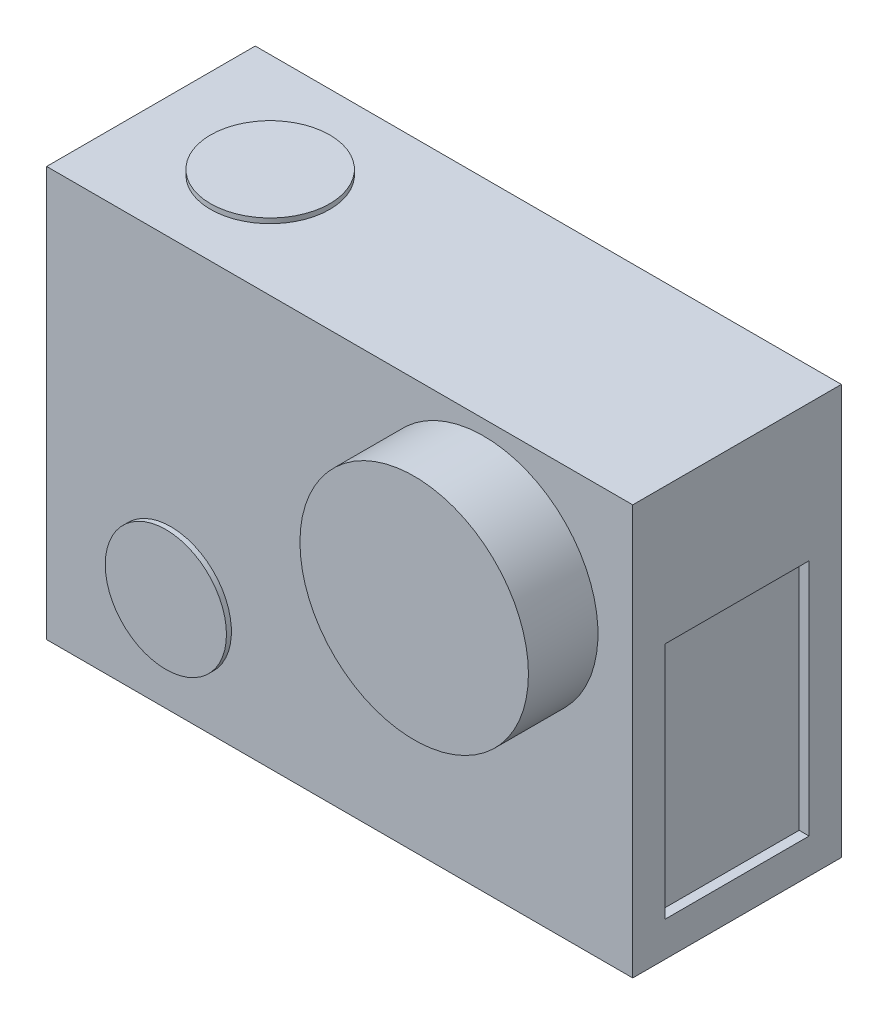
SolidWorks part; units mm, degrees
ref_plane "Front Plane" through (0, 0, 0) normal (0, 0, 1) x (1, 0, 0)
ref_plane "Top Plane" through (0, 0, 0) normal (0, 1, 0) x (1, 0, 0)
ref_plane "Right Plane" through (0, 0, 0) normal (1, 0, 0) x (0, 0, -1)
sketch "Sketch1" plane through (0, 0, 0) normal (0, 0, 1) x (1, 0, 0)
  line L1 (29.5, 20.625) -> (-29.5, 20.625)
  line L2 (29.5, 20.625) -> (29.5, -20.625)
  line L3 (29.5, -20.625) -> (-29.5, -20.625)
  line L4 (-29.5, 20.625) -> (-29.5, -20.625)
  line L5 (29.5, 20.625) -> (-29.5, -20.625) construction
  line L6 (29.5, -20.625) -> (-29.5, 20.625) construction
  point P0 (0, 0)
  dimension "D1" = 59
  dimension "D2" = 41.25
extrude "Boss-Extrude1" add sketch "Sketch1" along normal blind 21
sketch "Sketch2" plane through (0, 0, 21) normal (0, 0, 1) x (1, 0, 0)
  line L0 (29.5, -20.625) -> (29.5, 20.625) construction
  line L1 (29.5, 20.625) -> (-29.5, 20.625) construction
  circle A0 centre (14.5, 7.625) radius 11.5
  dimension "D3" = 23
  dimension "D1" = 15
  dimension "D2" = 13
extrude "Boss-Extrude2" add sketch "Sketch2" along normal blind 7
sketch "Sketch3" plane through (0, 0, 21) normal (0, 0, 1) x (1, 0, 0)
  line L0 (-29.5, 20.625) -> (-29.5, -20.625) construction
  line L2 (-29.5, -20.625) -> (29.5, -20.625) construction
  circle A0 centre (-17, -10.625) radius 6.1
  dimension "D3" = 12.2
  dimension "D1" = 12.5
  dimension "D2" = 10
extrude "Boss-Extrude3" add sketch "Sketch3" along normal blind 0.5
sketch "Sketch4" plane through (29.5, 0, 0) normal (1, 0, 0) x (0, 0, -1)
  line L0 (-10.5, 20.625) -> (-10.5, -49979.375) construction
  line L1 (-17.75, 6.875) -> (-3.25, 6.875)
  line L2 (-17.75, 6.875) -> (-17.75, -17.125)
  line L3 (-17.75, -17.125) -> (-3.25, -17.125)
  line L4 (-3.25, 6.875) -> (-3.25, -17.125)
  line L5 (-21, 20.625) -> (0, 20.625) construction
  line L6 (-21, -20.625) -> (0, -20.625) construction
  point P8 (-10.5, 20.625)
  dimension "D1" = 24
  dimension "D2" = 14.5
  dimension "D3" = 3.5
extrude "Cut-Extrude1" cut sketch "Sketch4" against normal blind 1
sketch "Sketch5" plane through (0, 0, 0) normal (0, 0, -1) x (-1, 0, 0)
  line L1 (23.5, 18.25) -> (-23.5, 18.25)
  line L2 (23.5, 18.25) -> (23.5, -18.25)
  line L3 (23.5, -18.25) -> (-23.5, -18.25)
  line L4 (-23.5, 18.25) -> (-23.5, -18.25)
  line L5 (23.5, 18.25) -> (-23.5, -18.25) construction
  line L6 (23.5, -18.25) -> (-23.5, 18.25) construction
  point P0 (0, 0)
  dimension "D1" = 47
  dimension "D2" = 36.5
extrude "Cut-Extrude2" cut sketch "Sketch5" against normal blind 0.2
sketch "Sketch6" plane through (0, 20.625, 0) normal (0, 1, 0) x (1, 0, 0)
  line L0 (-29.5, -21) -> (-29.5, 0) construction
  circle A0 centre (-17.5, -10.5) radius 6
  point P4 (-29.5, -10.5)
  dimension "D1" = 12
  dimension "D2" = 12
extrude "Boss-Extrude4" add sketch "Sketch6" along normal blind 0.5
